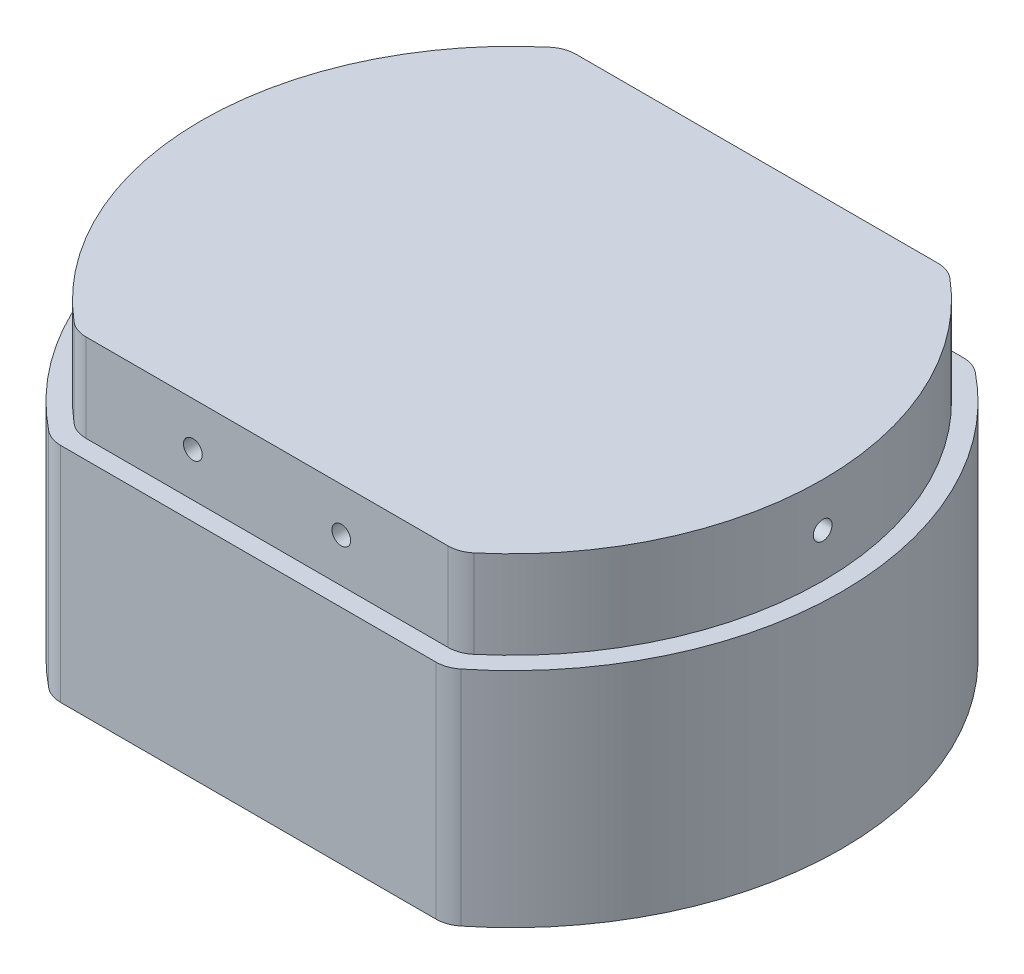
SolidWorks part; units mm, degrees
material "AISI 304"
ref_plane "Ön Düzlem" through (0, 0, 0) normal (0, 0, 1) x (1, 0, 0)
ref_plane "Üst Düzlem" through (0, 0, 0) normal (0, 1, 0) x (1, 0, 0)
ref_plane "Sağ Düzlem" through (0, 0, 0) normal (1, 0, 0) x (0, 0, -1)
sketch "Çizim1" plane through (0, 0, 0) normal (0, 1, 0) x (1, 0, 0)
  line L0 (0, 0) -> (0, 45) construction
  line L1 (-32.04, 45) -> (32.04, 45)
  line L2 (0, 0) -> (0, -45) construction
  line L3 (-32.04, -45) -> (32.04, -45)
  arc A0 (-35.1659, 43.9024) -> (-35.1659, -43.9024) centre (0, 0) ccw
  arc A1 (35.1659, -43.9024) -> (35.1659, 43.9024) centre (0, 0) ccw
  arc A2 (32.04, 45) -> (35.1659, 43.9024) centre (32.04, 40) cw
  arc A3 (32.04, -45) -> (35.1659, -43.9024) centre (32.04, -40) ccw
  arc A4 (-32.04, -45) -> (-35.1659, -43.9024) centre (-32.04, -40) cw
  arc A5 (-32.04, 45) -> (-35.1659, 43.9024) centre (-32.04, 40) ccw
  point P7 (0, 45)
  point P11 (0, -45)
  point P14 (33.75, -45)
  dimension "D1" = 112.5
  dimension "D3" = 5
  dimension "D2" = 45
extrude "Yükseklik-Ekstrüzyon1" add sketch "Çizim1" along normal blind 53
sketch "Çizim2" plane through (0, 53, 0) normal (0, 1, 0) x (1, 0, 0)
  line L0 (0, 0) -> (0, 45) construction
  line L1 (32.04, 45) -> (-32.04, 45) construction
  line L2 (0, 0) -> (-8.7249, 0) construction
  line L3 (33.75, 45) -> (-33.75, 45)
  line L4 (33.75, -45) -> (-33.75, -45)
  line L5 (32.6659, -41.8) -> (-32.6659, -41.8)
  line L6 (32.6659, 41.8) -> (-32.6659, 41.8)
  arc A0 (-33.75, 45) -> (-33.75, -45) centre (0, 0) ccw
  arc A1 (33.75, -45) -> (33.75, 45) centre (0, 0) ccw
  arc A2 (-32.6659, 41.8) -> (-32.6659, -41.8) centre (0, 0) ccw
  arc A3 (32.6659, -41.8) -> (32.6659, 41.8) centre (0, 0) ccw
  point P10 (0, 45)
  dimension "D1" = 112.5
  dimension "D2" = 3.2
extrude "Kes-Ekstrüzyon1" cut sketch "Çizim2" against normal blind 15
ref_plane "Düzlem1" through (56.25, 0, 0) normal (1, 0, 0) x (0, 0, -1)
sketch "Çizim6" plane through (0, 0, -41.8) normal (0, 0, -1) x (-1, 0, 0)
  line L0 (-12.6659, 53) -> (-12.6659, 45.5) construction
  line L1 (-32.6659, 53) -> (32.6659, 53) construction
  line L2 (-32.6659, 38) -> (-32.6659, 53) construction
  line L4 (12.6659, 53) -> (12.6659, 45.5) construction
  line L5 (32.6659, 38) -> (32.6659, 53) construction
  point P1 (-12.6659, 45.5)
  point P7 (12.6659, 45.5)
  point P12 (-12.6659, 45.5)
  point P16 (12.6659, 45.5)
  dimension "D1" = 20
  dimension "D2" = 20
  dimension "D3" = 7.5
hole_wizard "M3 Boşluklu Delik2" positions "Çizim6" profile "Çizim7" hole size "M3" standard "ISO"
sketch "Çizim7" plane through (-12.6659, 45.5, -41.8) normal (1, 0, 0) x (0, 1, 0)
  line L0 (0, 0) -> (0, 7.8614)
  line L1 (0, 7.8614) -> (1.6, 6.9)
  line L2 (1.6, 6.9) -> (1.6, 0)
  line L5 (1.6, 0) -> (0, 0)
  line L10 (0, 7.8614) -> (-1.6, 6.9) construction
  line L11 (0, -6.35) -> (0, 107.95) construction
  dimension "Hole Dia." = 3.2
  dimension "Hole Depth" = 6.9
  dimension "Drill Angle" = 118
sketch "Çizim9" plane through (0, 0, 41.8) normal (0, 0, 1) x (1, 0, 0)
  line L0 (-12.6659, 53) -> (-12.6659, 45.5) construction
  line L1 (-32.6659, 53) -> (32.6659, 53) construction
  line L2 (12.6659, 53) -> (12.6659, 45.5) construction
  line L3 (-32.6659, 38) -> (-32.6659, 53) construction
  line L4 (32.6659, 38) -> (32.6659, 53) construction
  point P1 (-12.6659, 45.5)
  point P5 (12.6659, 45.5)
  point P12 (-12.6659, 45.5)
  point P16 (12.6659, 45.5)
  dimension "D1" = 7.5
  dimension "D2" = 7.5
  dimension "D3" = 20
  dimension "D4" = 20
hole_wizard "M3 Boşluklu Delik1" positions "Çizim9" profile "Çizim10" hole size "M3" standard "ISO"
sketch "Çizim10" plane through (12.6659, 45.5, 41.8) normal (1, 0, 0) x (0, -1, 0)
  line L0 (0, 0) -> (0, 7.8614)
  line L1 (0, 7.8614) -> (1.6, 6.9)
  line L2 (1.6, 6.9) -> (1.6, 0)
  line L5 (1.6, 0) -> (0, 0)
  line L10 (0, 7.8614) -> (-1.6, 6.9) construction
  line L11 (0, -6.35) -> (0, 107.95) construction
  dimension "Hole Dia." = 3.2
  dimension "Hole Depth" = 6.9
  dimension "Drill Angle" = 118
sketch "Çizim11" plane through (0, 0, 41.8) normal (0, 0, 1) x (1, 0, 0)
  line L0 (0, 38) -> (0, 45.5) construction
  line L1 (-32.04, 38) -> (32.04, 38) construction
  line L2 (0, 45.5) -> (-12.6659, 45.5) construction
  dimension "D1" = 7.5
fillet "Radyus1" radius 5 4 edges at (-32.6659, 45.5, -41.8) (32.6659, 45.5, -41.8) (32.6659, 45.5, 41.8) (-32.6659, 45.5, 41.8)
ref_plane "Düzlem3" through (53.05, 0, 0) normal (1, 0, 0) x (0, 0, -1)
sketch "Çizim16" plane through (0, 53, 0) normal (0, 1, 0) x (1, 0, 0)
  line L0 (0, 0) -> (53.05, 0) construction
  line L1 (53.05, -29.15) -> (53.05, 29.15) construction
sketch "Çizim17" plane through (53.05, 0, 0) normal (1, 0, 0) x (0, 0, -1)
  line L0 (0, 53) -> (0, 45.5) construction
  line L1 (40.6293, 53) -> (-40.6293, 53) construction
  point P1 (0, 45.5)
  point P10 (0, 45.5)
  dimension "D1" = 7.5
hole_wizard "M3 Boşluklu Delik3" positions "Çizim17" profile "Çizim19" hole size "M3" standard "ISO"
sketch "Çizim19" plane through (53.05, 45.5, 0) normal (0, 1, 0) x (0, 0, -1)
  line L0 (0, 0) -> (0, 12.7614)
  line L1 (0, 12.7614) -> (1.6, 11.8)
  line L2 (1.6, 11.8) -> (1.6, 0)
  line L5 (1.6, 0) -> (0, 0)
  line L10 (0, 12.7614) -> (-1.6, 11.8) construction
  line L11 (0, -6.35) -> (0, 107.95) construction
  dimension "Hole Dia." = 3.2
  dimension "Hole Depth" = 11.8
  dimension "Drill Angle" = 118
pattern_circular "Dairesel Kaplama1" count 2 over 180 about axis through (0, 53, 0) along (0, 1, 0) of "M3 Boşluklu Delik3"
